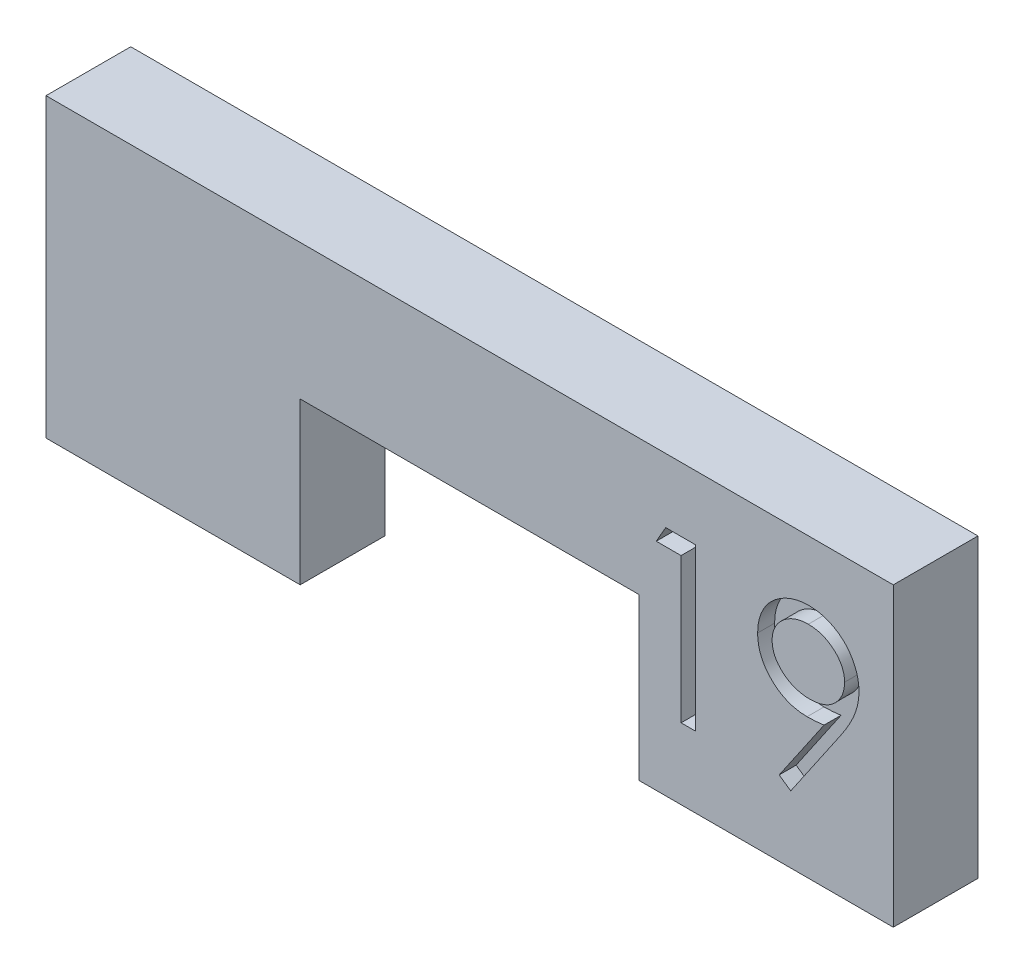
SolidWorks part; units mm, degrees
ref_plane "Front Plane" through (0, 0, 0) normal (0, 0, 1) x (1, 0, 0)
ref_plane "Top Plane" through (0, 0, 0) normal (0, 1, 0) x (1, 0, 0)
ref_plane "Right Plane" through (0, 0, 0) normal (1, 0, 0) x (0, 0, -1)
sketch "Sketch2" plane through (0, 0, 0) normal (0, 0, 1) x (1, 0, 0)
  line L0 (0, 42.3611) -> (0, -10.2822) construction
  line L1 (50, 35) -> (-50, 35)
  line L2 (-50, 35) -> (-50, 0)
  line L3 (-50, 0) -> (-20, 0)
  line L4 (-20, 0) -> (-20, 19)
  line L5 (-20, 19) -> (20, 19)
  line L6 (20, 0) -> (20, 19)
  line L7 (50, 0) -> (20, 0)
  line L8 (50, 35) -> (50, 0)
  point P11 (0, 19)
  point P14 (0, 35)
  dimension "D1" = 50
  dimension "D2" = 20
  dimension "D3" = 35
  dimension "D4" = 19
extrude "Boss-Extrude1" add sketch "Sketch2" along normal blind 10
sketch "Sketch3" plane through (0, 0, 10) normal (0, 0, 1) x (1, 0, 0)
  text T0 "19" font "Century Gothic" height in points 72
extrude "Cut-Extrude1" cut sketch "Sketch3" against normal blind 2
